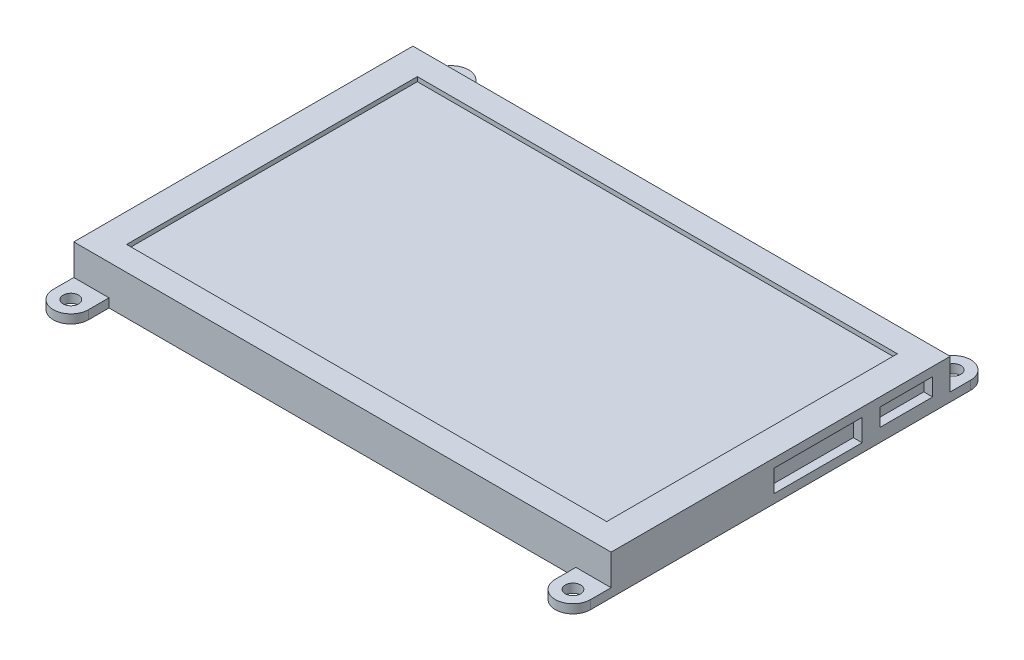
SolidWorks part; units mm, degrees
ref_plane "Front Plane" through (0, 0, 0) normal (0, 0, 1) x (1, 0, 0)
ref_plane "Top Plane" through (0, 0, 0) normal (0, 1, 0) x (1, 0, 0)
ref_plane "Right Plane" through (0, 0, 0) normal (1, 0, 0) x (0, 0, -1)
sketch "Sketch1" plane through (0, 0, 0) normal (0, 1, 0) x (1, 0, 0)
  line L1 (0, 0) -> (122, 0)
  line L2 (0, 0) -> (0, 77)
  line L3 (0, 77) -> (122, 77)
  line L4 (122, 0) -> (122, 77)
  dimension "D1" = 77
  dimension "D2" = 122
extrude "Boss-Extrude1" add sketch "Sketch1" along normal blind 9 contours L3 L4 L1 L2
sketch "Sketch2" plane through (0, 9, 0) normal (0, 1, 0) x (1, 0, 0)
  line L0 (61, 77) -> (61, 0) construction
  line L1 (0, 77) -> (122, 77) construction
  line L2 (0, 0) -> (122, 0) construction
  line L3 (0, 38.5) -> (122, 38.5) construction
  line L4 (0, 0) -> (0, 77) construction
  line L5 (122, 0) -> (122, 77) construction
  line L7 (6.5, 71.5) -> (115.5, 71.5)
  line L8 (6.5, 71.5) -> (6.5, 5.5)
  line L9 (6.5, 5.5) -> (115.5, 5.5)
  line L10 (115.5, 71.5) -> (115.5, 5.5)
  line L11 (6.5, 71.5) -> (115.5, 5.5) construction
  line L12 (6.5, 5.5) -> (115.5, 71.5) construction
  point P12 (61, 38.5)
  dimension "D1" = 109
  dimension "D2" = 66
extrude "Cut-Extrude1" cut sketch "Sketch2" against normal blind 1
sketch "Sketch3" plane through (0, 0, 0) normal (0, -1, 0) x (1, 0, 0)
  line L0 (4, -81.66) -> (4, -72.34) construction
  line L1 (0, -81.66) -> (0, -72.34)
  line L2 (8, -81.66) -> (8, -72.34)
  line L3 (0, -77) -> (122, -77) construction
  line L4 (61, -77) -> (61, 9.2683) construction
  line L5 (122, -38.5) -> (0, -38.5) construction
  line L6 (122, 0) -> (122, -77) construction
  line L7 (0, 0) -> (0, -77) construction
  line L8 (118, -81.66) -> (118, -72.34) construction
  line L9 (122, -81.66) -> (122, -72.34)
  line L10 (114, -81.66) -> (114, -72.34)
  line L11 (4, 4.66) -> (4, -4.66) construction
  line L12 (0, 4.66) -> (0, -4.66)
  line L13 (8, 4.66) -> (8, -4.66)
  line L14 (118, 4.66) -> (118, -4.66) construction
  line L15 (122, 4.66) -> (122, -4.66)
  line L16 (114, 4.66) -> (114, -4.66)
  arc A0 (0, -81.66) -> (8, -81.66) centre (4, -81.66) ccw
  arc A1 (8, -72.34) -> (0, -72.34) centre (4, -72.34) ccw
  arc A2 (122, -81.66) -> (114, -81.66) centre (118, -81.66) cw
  arc A3 (114, -72.34) -> (122, -72.34) centre (118, -72.34) cw
  arc A4 (0, 4.66) -> (8, 4.66) centre (4, 4.66) cw
  arc A5 (8, -4.66) -> (0, -4.66) centre (4, -4.66) cw
  arc A6 (122, 4.66) -> (114, 4.66) centre (118, 4.66) ccw
  arc A7 (114, -4.66) -> (122, -4.66) centre (118, -4.66) ccw
  point P2 (4, -77)
  point P7 (0, -77)
  point P8 (4, -85.66)
  point P22 (118, -77)
  point P29 (4, 0)
  point P36 (118, 0)
  dimension "D1" = 8.66
  dimension "D2" = 8
extrude "Boss-Extrude2" add sketch "Sketch3" against normal blind 2
sketch "Sketch4" plane through (0, 0, 0) normal (0, -1, 0) x (1, 0, 0)
  line L0 (61, -77) -> (61, 0) construction
  line L1 (8, -77) -> (114, -77) construction
  line L2 (8, 0) -> (114, 0) construction
  line L3 (122, -38.5) -> (0, -38.5) construction
  line L4 (122, 4.66) -> (122, -81.66) construction
  line L5 (0, 4.66) -> (0, -81.66) construction
  circle A0 centre (4, -81.66) radius 1.75
  circle A1 centre (118, -81.66) radius 1.75
  circle A2 centre (4, 4.66) radius 1.75
  circle A3 centre (118, 4.66) radius 1.75
  dimension "D1" = 3.5
extrude "Cut-Extrude3" cut sketch "Sketch4" against normal blind 4 contours A1 | A3 | A2 | A0
sketch "Sketch5" plane through (122, 0, 0) normal (1, 0, 0) x (0, 0, -1)
  line L0 (77, 9) -> (77, 2) construction
  line L1 (73, 7) -> (61, 7)
  line L2 (73, 7) -> (73, 3)
  line L3 (73, 3) -> (61, 3)
  line L4 (61, 7) -> (61, 3)
  line L5 (73, 7) -> (61, 3) construction
  line L6 (73, 3) -> (61, 7) construction
  line L7 (57, 7) -> (37, 7)
  line L8 (57, 7) -> (57, 2)
  line L9 (57, 2) -> (37, 2)
  line L10 (37, 7) -> (37, 2)
  line L11 (57, 7) -> (37, 2) construction
  line L12 (57, 2) -> (37, 7) construction
  line L13 (-4.66, 0) -> (81.66, 0) construction
  point P0 (67, 5)
  point P5 (47, 4.5)
  point P14 (73, 5)
  dimension "D1" = 20
  dimension "D2" = 5
  dimension "D3" = 20
  dimension "D4" = 2
  dimension "D5" = 12
  dimension "D6" = 4
  dimension "D7" = 4
  dimension "D8" = 3
extrude "Cut-Extrude4" cut sketch "Sketch5" against normal blind 2
sketch "Sketch7" plane through (0, 0, 0) normal (0, -1, 0) x (1, 0, 0)
  line L1 (122, 4.66) -> (122, -81.66) construction
  line L3 (8, -77) -> (114, -77) construction
  circle A2 centre (66, -40) radius 3
  dimension "D1" = 6
  dimension "D2" = 56
  dimension "D3" = 37
extrude "Boss-Extrude3" [suppressed] add sketch "Sketch7" along normal blind 8
sketch "Sketch9" [suppressed] plane through (0, -8, 0) normal (0, -1, 0) x (1, 0, 0)
  line L0 (122, 4.66) -> (122, -81.66) construction
  line L3 (8, -77) -> (114, -77) construction
  circle A1 centre (66.5, -40.5) radius 1.6
  dimension "D1" = 3.2
  dimension "D3" = 36.5
  dimension "D2" = 55.5
extrude "Cut-Extrude5" [suppressed] cut sketch "Sketch9" against normal blind 8
